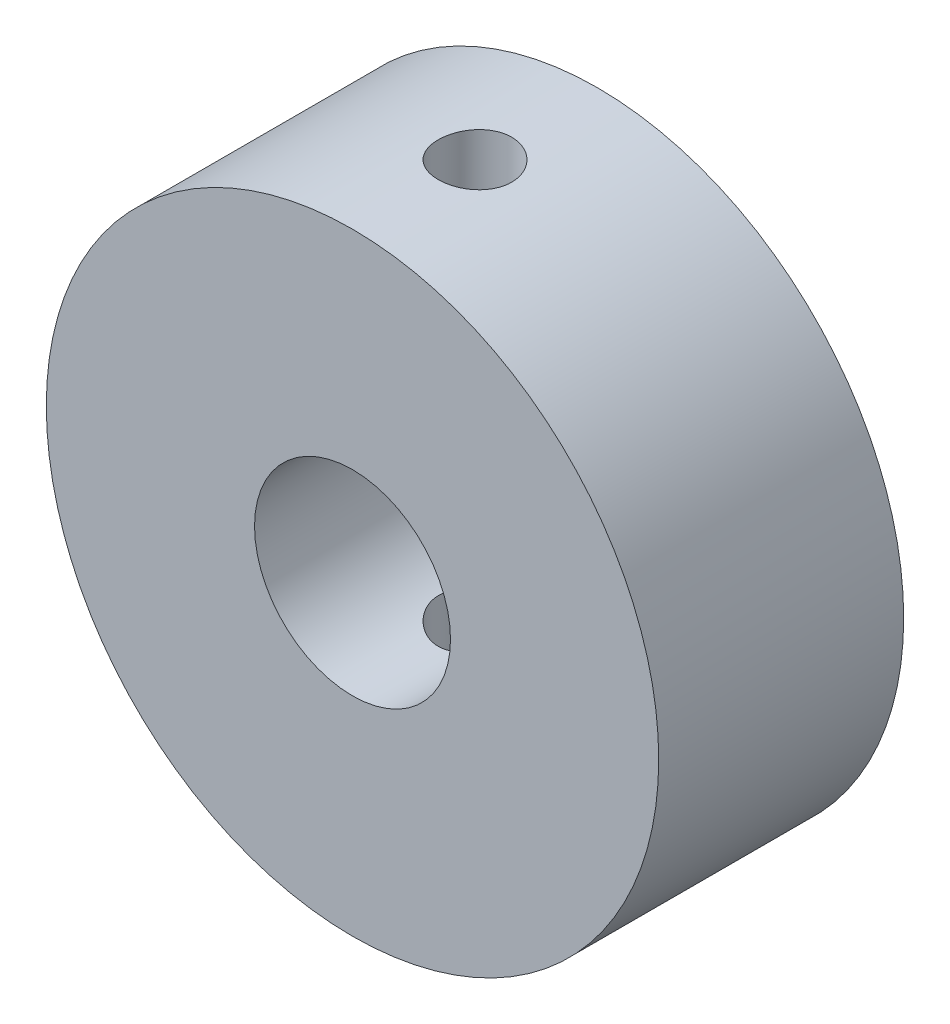
SolidWorks part; units mm, degrees
ref_plane "Front Plane" through (0, 0, 0) normal (0, 0, 1) x (1, 0, 0)
ref_plane "Top Plane" through (0, 0, 0) normal (0, 1, 0) x (1, 0, 0)
ref_plane "Right Plane" through (0, 0, 0) normal (1, 0, 0) x (0, 0, -1)
sketch "Sketch1" plane through (0, 0, 0) normal (0, 0, 1) x (1, 0, 0)
  circle A0 centre (0, 0) radius 12.5
  circle A1 centre (0, 0) radius 4
extrude "Boss-Extrude1" add sketch "Sketch1" along normal mid plane 10
sketch "Sketch2" plane through (0, 0, 0) normal (0, 1, 0) x (1, 0, 0)
  line L0 (12.5, 5) -> (-12.5, 5) construction
  circle A0 centre (0, 0) radius 1.5
  dimension "D1" = 5
  dimension "D2" = 3
extrude "Cut-Extrude1" cut sketch "Sketch2" against normal blind 17 and the other way blind 14
